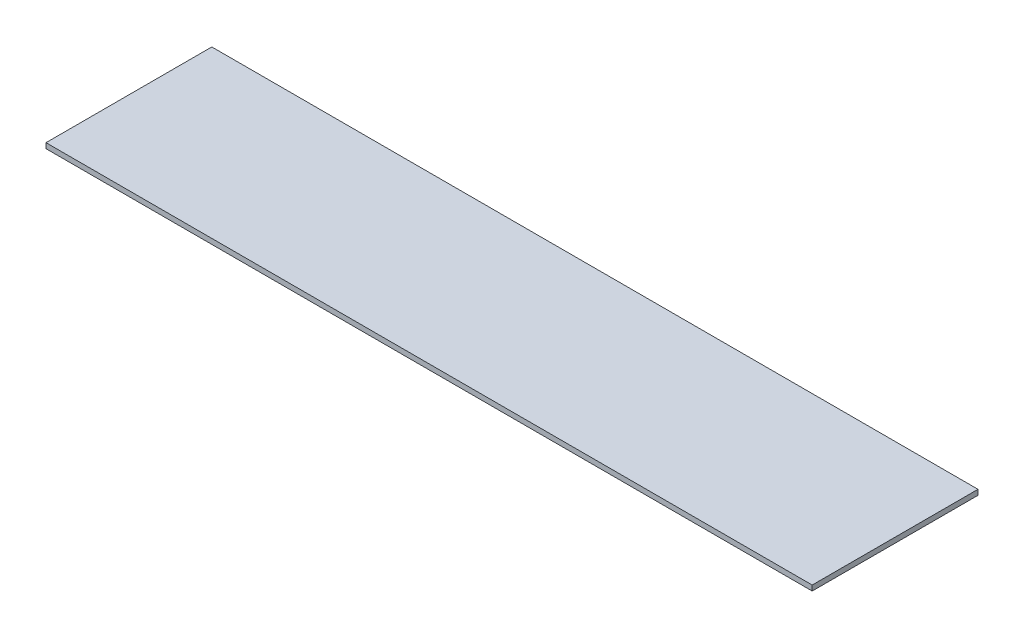
SolidWorks part; units mm, degrees
ref_plane "Alzado" through (0, 0, 0) normal (0, 0, 1) x (1, 0, 0)
ref_plane "Planta" through (0, 0, 0) normal (0, 1, 0) x (1, 0, 0)
ref_plane "Vista lateral" through (0, 0, 0) normal (1, 0, 0) x (0, 0, -1)
sketch "Croquis1" plane through (0, 0, 0) normal (0, 1, 0) x (1, 0, 0)
  line L1 (219.5, -47.5) -> (-219.5, -47.5)
  line L2 (219.5, -47.5) -> (219.5, 47.5)
  line L3 (219.5, 47.5) -> (-219.5, 47.5)
  line L4 (-219.5, -47.5) -> (-219.5, 47.5)
  line L5 (219.5, -47.5) -> (-219.5, 47.5) construction
  line L6 (219.5, 47.5) -> (-219.5, -47.5) construction
  point P0 (0, 0)
extrude "Saliente-Extruir1" add sketch "Croquis1" along normal blind 3
